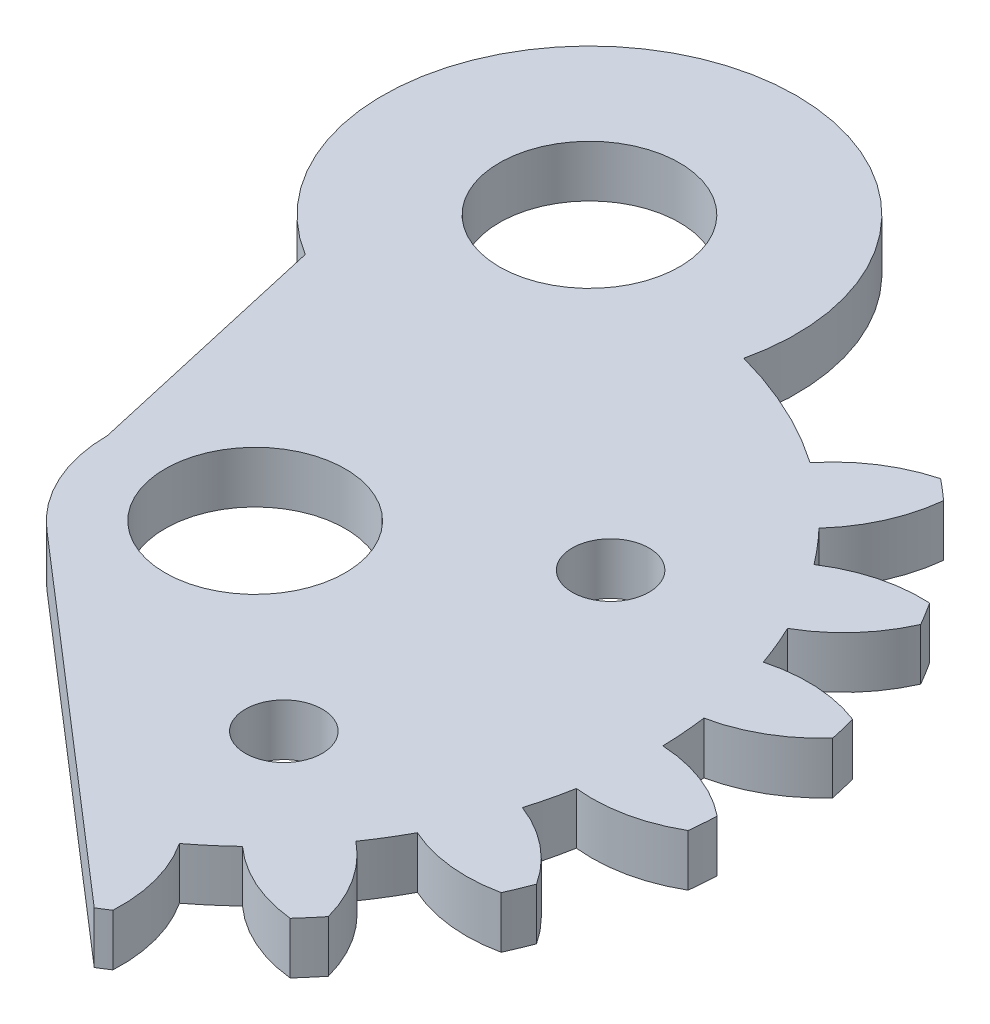
SolidWorks part; units mm, degrees
ref_plane "前视基准面" through (0, 0, 0) normal (0, 0, 1) x (1, 0, 0)
ref_plane "上视基准面" through (0, 0, 0) normal (0, 1, 0) x (1, 0, 0)
ref_plane "右视基准面" through (0, 0, 0) normal (1, 0, 0) x (0, 0, -1)
other "Configuration Table"
sketch "草图1" plane through (0, 0, 0) normal (0, 1, 0) x (1, 0, 0)
  line L0 (0, 0) -> (0, 56.9379) construction
  line L1 (0, 0) -> (19.4661, 53.4826) construction
  line L2 (0, 0) -> (4.4104, 56.0389) construction
  line L3 (0, 30) -> (9.6418, 26.4907) construction
  circle A0 centre (0, 0) radius 30 construction
  circle A1 centre (0, 0) radius 27
  circle A2 centre (0, 0) radius 33
  arc A3 (1.6756, 32.9574) -> (-0.6065, 26.9932) centre (9.6418, 26.4907) ccw
  arc A4 (3.5007, 32.8138) -> (4.8217, 26.566) centre (-5.3791, 27.6728) cw
  dimension "D1" = 60
  dimension "D2" = 3
  dimension "D3" = 3
  dimension "D4" = 20
  dimension "D5" = 4.5
extrude "凸台-拉伸2" add sketch "草图1" along normal blind 10 contours A1
sketch "草图3" plane through (0, 10, 0) normal (0, 1, 0) x (1, 0, 0)
  arc A0 (4.8217, 26.566) -> (3.5007, 32.8138) centre (-5.3791, 27.6728) ccw construction
  circle A1 centre (0, 0) radius 33
  circle A2 centre (0, 0) radius 33
  circle A3 centre (0, 0) radius 27
  circle A4 centre (0, 0) radius 27
  arc A5 (1.6756, 32.9574) -> (-0.6065, 26.9932) centre (9.6418, 26.4907) ccw construction
  arc A6 (4.8217, 26.566) -> (3.5007, 32.8138) centre (-5.3791, 27.6728) ccw
  arc A7 (1.6756, 32.9574) -> (-0.6065, 26.9932) centre (9.6418, 26.4907) ccw
  arc A8 (12.795, 23.7758) -> (13.4694, 30.126) centre (3.4356, 27.9806) ccw
  arc A9 (11.778, 30.8266) -> (7.7646, 25.8595) centre (17.356, 22.2146) ccw
  arc A10 (19.5159, 18.6582) -> (22.1196, 24.4892) centre (11.9139, 25.5495) ccw
  arc A11 (20.7275, 25.6782) -> (15.3755, 22.1944) centre (23.3712, 15.7641) ccw
  arc A12 (24.3264, 11.7143) -> (28.6046, 16.4553) centre (19.2261, 20.6174) ccw
  arc A13 (27.648, 18.0163) -> (21.4815, 16.3568) centre (27.0987, 7.7704) ccw
  arc A14 (26.7557, 3.6237) -> (32.2896, 6.8106) centre (24.6562, 13.6672) ccw
  arc A15 (31.8622, 8.5908) -> (25.4846, 8.9181) centre (28.1736, -0.9838) ccw
  arc A16 (26.566, -4.8217) -> (32.8138, -3.5007) centre (27.6728, 5.3791) ccw
  arc A17 (32.9574, -1.6756) -> (26.9932, 0.6065) centre (26.4907, -9.6418) ccw
  arc A18 (23.7758, -12.795) -> (30.126, -13.4694) centre (27.9806, -3.4356) ccw
  arc A19 (30.8266, -11.778) -> (25.8595, -7.7646) centre (22.2146, -17.356) ccw
  arc A20 (18.6582, -19.5159) -> (24.4892, -22.1196) centre (25.5495, -11.9139) ccw
  arc A21 (25.6782, -20.7275) -> (22.1944, -15.3755) centre (15.7641, -23.3712) ccw
  arc A22 (11.7143, -24.3264) -> (16.4553, -28.6046) centre (20.6174, -19.2261) ccw
  arc A23 (18.0163, -27.648) -> (16.3568, -21.4815) centre (7.7704, -27.0987) ccw
  arc A24 (3.6237, -26.7557) -> (6.8106, -32.2896) centre (13.6672, -24.6562) ccw
  arc A25 (8.5908, -31.8622) -> (8.9181, -25.4846) centre (-0.9838, -28.1736) ccw
  arc A26 (-4.8217, -26.566) -> (-3.5007, -32.8138) centre (5.3791, -27.6728) ccw
  arc A27 (-1.6756, -32.9574) -> (0.6065, -26.9932) centre (-9.6418, -26.4907) ccw
  arc A28 (-12.795, -23.7758) -> (-13.4694, -30.126) centre (-3.4356, -27.9806) ccw
  arc A29 (-11.778, -30.8266) -> (-7.7646, -25.8595) centre (-17.356, -22.2146) ccw
  arc A30 (-19.5159, -18.6582) -> (-22.1196, -24.4892) centre (-11.9139, -25.5495) ccw
  arc A31 (-20.7275, -25.6782) -> (-15.3755, -22.1944) centre (-23.3712, -15.7641) ccw
  arc A32 (-24.3264, -11.7143) -> (-28.6046, -16.4553) centre (-19.2261, -20.6174) ccw
  arc A33 (-27.648, -18.0163) -> (-21.4815, -16.3568) centre (-27.0987, -7.7704) ccw
  arc A34 (-26.7557, -3.6237) -> (-32.2896, -6.8106) centre (-24.6562, -13.6672) ccw
  arc A35 (-31.8622, -8.5908) -> (-25.4846, -8.9181) centre (-28.1736, 0.9838) ccw
  arc A36 (-26.566, 4.8217) -> (-32.8138, 3.5007) centre (-27.6728, -5.3791) ccw
  arc A37 (-32.9574, 1.6756) -> (-26.9932, -0.6065) centre (-26.4907, 9.6418) ccw
  arc A38 (-23.7758, 12.795) -> (-30.126, 13.4694) centre (-27.9806, 3.4356) ccw
  arc A39 (-30.8266, 11.778) -> (-25.8595, 7.7646) centre (-22.2146, 17.356) ccw
  arc A40 (-18.6582, 19.5159) -> (-24.4892, 22.1196) centre (-25.5495, 11.9139) ccw
  arc A41 (-25.6782, 20.7275) -> (-22.1944, 15.3755) centre (-15.7641, 23.3712) ccw
  arc A42 (-11.7143, 24.3264) -> (-16.4553, 28.6046) centre (-20.6174, 19.2261) ccw
  arc A43 (-18.0163, 27.648) -> (-16.3568, 21.4815) centre (-7.7704, 27.0987) ccw
  arc A44 (-3.6237, 26.7557) -> (-6.8106, 32.2896) centre (-13.6672, 24.6562) ccw
  arc A45 (-8.5908, 31.8622) -> (-8.9181, 25.4846) centre (0.9838, 28.1736) ccw
  point P129 (0, 0)
  circle M3 centre (0, 0) radius 27
  dimension "D1" = 0
  dimension "D2" = 0
  dimension "D3" = 20
extrude "凸台-拉伸3" add sketch "草图3" against normal blind 10 contours A2 A45 A44 M3 | A2 A43 A42 M3 | A2 A41 A40 M3 | A2 A39 A38 M3 | A2 A37 A36 M3 | A2 A35 A34 M3 | A2 A33 A32 M3 | A2 A31 A30 M3 | A2 A29 A28 M3 | A2 A27 A26 M3 | A2 A25 A24 M3 | A2 A23 A22 M3 | A2 A21 A20 M3 | A2 A19 A18 M3 | A2 A17 A16 M3 | A2 A15 A14 M3 | A2 A13 A12 M3 | A2 A11 A10 M3 | A2 A9 A8 M3 | A2 A7 A6 M3
sketch "草图4" plane through (0, 10, 0) normal (0, 1, 0) x (1, 0, 0)
  line L0 (0, 0) -> (23.0213, -14.1075)
  line L1 (0, 0) -> (-2.1184, 26.9168)
  line L2 (-9.5508, 2.9635) -> (19.9356, 97.9927)
  line L5 (-6.5422, -7.5631) -> (68.7094, -72.6568)
  arc A0 (16.4553, -28.6046) -> (18.0163, -27.648) centre (0, 0) ccw construction
  arc A1 (-0.6065, 26.9932) -> (-3.6237, 26.7557) centre (0, 0) ccw construction
  circle A2 centre (0, 0) radius 100
  arc A3 (22.1944, -15.3755) -> (23.7758, -12.795) centre (0, 0) ccw construction
  circle A4 centre (0, 0) radius 10
  point P9 (17.2425, -28.1371)
  point P18 (-2.1184, 26.9168)
  dimension "D1" = 20
  dimension "D2" = 200
extrude "切除-拉伸2" cut sketch "草图4" against normal through all
sketch "草图6" plane through (0, 10, 0) normal (0, 1, 0) x (1, 0, 0)
  line L2 (-6.5422, -7.5631) -> (17.2425, -28.1371)
  line L3 (-2.1184, 26.9168) -> (-9.5508, 2.9635)
  line L4 (-6.5422, -7.5631) -> (17.2425, -28.1371)
  line L5 (-2.1184, 26.9168) -> (-9.5508, 2.9635)
  circle A0 centre (0, 0) radius 6.1
  arc A22 (-9.5508, 2.9635) -> (-6.5422, -7.5631) centre (0, 0) ccw
  arc A23 (17.2425, -28.1371) -> (18.0163, -27.648) centre (0, 0) ccw
  arc A24 (30.8266, -11.778) -> (25.8595, -7.7646) centre (22.2146, -17.356) ccw
  arc A25 (25.8595, -7.7646) -> (26.566, -4.8217) centre (0, 0) ccw
  arc A26 (26.566, -4.8217) -> (32.8138, -3.5007) centre (27.6728, 5.3791) ccw
  arc A27 (32.8138, -3.5007) -> (32.9574, -1.6756) centre (0, 0) ccw
  arc A28 (32.9574, -1.6756) -> (26.9932, 0.6065) centre (26.4907, -9.6418) ccw
  arc A29 (26.9932, 0.6065) -> (26.7557, 3.6237) centre (0, 0) ccw
  arc A30 (26.7557, 3.6237) -> (32.2896, 6.8106) centre (24.6562, 13.6672) ccw
  arc A31 (32.2896, 6.8106) -> (31.8622, 8.5908) centre (0, 0) ccw
  arc A32 (31.8622, 8.5908) -> (25.4846, 8.9181) centre (28.1736, -0.9838) ccw
  arc A33 (25.4846, 8.9181) -> (24.3264, 11.7143) centre (0, 0) ccw
  arc A34 (24.3264, 11.7143) -> (28.6046, 16.4553) centre (19.2261, 20.6174) ccw
  arc A35 (28.6046, 16.4553) -> (27.648, 18.0163) centre (0, 0) ccw
  arc A36 (27.648, 18.0163) -> (21.4815, 16.3568) centre (27.0987, 7.7704) ccw
  arc A37 (21.4815, 16.3568) -> (19.5159, 18.6582) centre (0, 0) ccw
  arc A38 (19.5159, 18.6582) -> (22.1196, 24.4892) centre (11.9139, 25.5495) ccw
  arc A39 (22.1196, 24.4892) -> (20.7275, 25.6782) centre (0, 0) ccw
  arc A40 (20.7275, 25.6782) -> (15.3755, 22.1944) centre (23.3712, 15.7641) ccw
  arc A41 (15.3755, 22.1944) -> (12.795, 23.7758) centre (0, 0) ccw
  arc A42 (12.795, 23.7758) -> (13.4694, 30.126) centre (3.4356, 27.9806) ccw
  arc A43 (13.4694, 30.126) -> (11.778, 30.8266) centre (0, 0) ccw
  arc A44 (-9.5508, 2.9635) -> (-6.5422, -7.5631) centre (0, 0) ccw
  arc A45 (17.2425, -28.1371) -> (18.0163, -27.648) centre (0, 0) ccw
  arc A46 (30.8266, -11.778) -> (25.8595, -7.7646) centre (22.2146, -17.356) ccw
  arc A47 (25.8595, -7.7646) -> (26.566, -4.8217) centre (0, 0) ccw
  arc A48 (26.566, -4.8217) -> (32.8138, -3.5007) centre (27.6728, 5.3791) ccw
  arc A49 (32.8138, -3.5007) -> (32.9574, -1.6756) centre (0, 0) ccw
  arc A50 (32.9574, -1.6756) -> (26.9932, 0.6065) centre (26.4907, -9.6418) ccw
  arc A51 (26.9932, 0.6065) -> (26.7557, 3.6237) centre (0, 0) ccw
  arc A52 (26.7557, 3.6237) -> (32.2896, 6.8106) centre (24.6562, 13.6672) ccw
  arc A53 (32.2896, 6.8106) -> (31.8622, 8.5908) centre (0, 0) ccw
  arc A54 (31.8622, 8.5908) -> (25.4846, 8.9181) centre (28.1736, -0.9838) ccw
  arc A55 (25.4846, 8.9181) -> (24.3264, 11.7143) centre (0, 0) ccw
  arc A56 (24.3264, 11.7143) -> (28.6046, 16.4553) centre (19.2261, 20.6174) ccw
  arc A57 (28.6046, 16.4553) -> (27.648, 18.0163) centre (0, 0) ccw
  arc A58 (27.648, 18.0163) -> (21.4815, 16.3568) centre (27.0987, 7.7704) ccw
  arc A59 (21.4815, 16.3568) -> (19.5159, 18.6582) centre (0, 0) ccw
  arc A60 (19.5159, 18.6582) -> (22.1196, 24.4892) centre (11.9139, 25.5495) ccw
  arc A61 (22.1196, 24.4892) -> (20.7275, 25.6782) centre (0, 0) ccw
  arc A62 (20.7275, 25.6782) -> (15.3755, 22.1944) centre (23.3712, 15.7641) ccw
  arc A63 (15.3755, 22.1944) -> (12.795, 23.7758) centre (0, 0) ccw
  arc A64 (12.795, 23.7758) -> (13.4694, 30.126) centre (3.4356, 27.9806) ccw
  arc A65 (13.4694, 30.126) -> (11.778, 30.8266) centre (0, 0) ccw
  arc A73 (11.778, 30.8266) -> (7.7646, 25.8595) centre (17.356, 22.2146) ccw
  arc A74 (11.778, 30.8266) -> (7.7646, 25.8595) centre (17.356, 22.2146) ccw
  arc A75 (7.7646, 25.8595) -> (4.8217, 26.566) centre (0, 0) ccw
  arc A76 (7.7646, 25.8595) -> (4.8217, 26.566) centre (0, 0) ccw
  arc A77 (4.8217, 26.566) -> (3.5007, 32.8138) centre (-5.3791, 27.6728) ccw
  arc A78 (4.8217, 26.566) -> (3.5007, 32.8138) centre (-5.3791, 27.6728) ccw
  arc A79 (3.5007, 32.8138) -> (1.6756, 32.9574) centre (0, 0) ccw
  arc A80 (3.5007, 32.8138) -> (1.6756, 32.9574) centre (0, 0) ccw
  arc A81 (1.6756, 32.9574) -> (-0.6065, 26.9932) centre (9.6418, 26.4907) ccw
  arc A82 (1.6756, 32.9574) -> (-0.6065, 26.9932) centre (9.6418, 26.4907) ccw
  arc A83 (-0.6065, 26.9932) -> (-2.1184, 26.9168) centre (0, 0) ccw
  arc A84 (-0.6065, 26.9932) -> (-2.1184, 26.9168) centre (0, 0) ccw
  arc A89 (25.6782, -20.7275) -> (22.1944, -15.3755) centre (15.7641, -23.3712) ccw
  arc A90 (25.6782, -20.7275) -> (22.1944, -15.3755) centre (15.7641, -23.3712) ccw
  arc A91 (22.1944, -15.3755) -> (23.7758, -12.795) centre (0, 0) ccw
  arc A92 (22.1944, -15.3755) -> (23.7758, -12.795) centre (0, 0) ccw
  arc A93 (23.7758, -12.795) -> (30.126, -13.4694) centre (27.9806, -3.4356) ccw
  arc A94 (23.7758, -12.795) -> (30.126, -13.4694) centre (27.9806, -3.4356) ccw
  arc A95 (30.126, -13.4694) -> (30.8266, -11.778) centre (0, 0) ccw
  arc A96 (30.126, -13.4694) -> (30.8266, -11.778) centre (0, 0) ccw
  arc A101 (18.0163, -27.648) -> (16.3568, -21.4815) centre (7.7704, -27.0987) ccw
  arc A102 (18.0163, -27.648) -> (16.3568, -21.4815) centre (7.7704, -27.0987) ccw
  arc A103 (16.3568, -21.4815) -> (18.6582, -19.5159) centre (0, 0) ccw
  arc A104 (16.3568, -21.4815) -> (18.6582, -19.5159) centre (0, 0) ccw
  arc A105 (18.6582, -19.5159) -> (24.4892, -22.1196) centre (25.5495, -11.9139) ccw
  arc A106 (18.6582, -19.5159) -> (24.4892, -22.1196) centre (25.5495, -11.9139) ccw
  arc A107 (24.4892, -22.1196) -> (25.6782, -20.7275) centre (0, 0) ccw
  arc A108 (24.4892, -22.1196) -> (25.6782, -20.7275) centre (0, 0) ccw
  dimension "D2" = 12.2
  dimension "D1" = 0
extrude "切除-拉伸3" cut sketch "草图6" against normal blind 10 contours A0
sketch "草图9" plane through (0, 10, 0) normal (0, 1, 0) x (1, 0, 0)
  line L0 (-10, 0) -> (-18.3373, 36.811)
  line L1 (-6.5422, -7.5631) -> (4.8217, 26.566)
  line L2 (4.8217, 26.566) -> (7.168, 33.6128)
  line L3 (-6.5422, -7.5631) -> (17.2425, -28.1371)
  line L4 (-2.1184, 26.9168) -> (-9.5508, 2.9635)
  line L5 (-6.5422, -7.5631) -> (17.2425, -28.1371)
  line L6 (-2.1184, 26.9168) -> (-9.5508, 2.9635)
  arc A0 (-9.5508, 2.9635) -> (-6.5422, -7.5631) centre (0, 0) ccw construction
  circle A1 centre (-10, 0) radius 37.7433
  arc A42 (-9.5508, 2.9635) -> (-6.5422, -7.5631) centre (0, 0) ccw
  arc A43 (17.2425, -28.1371) -> (18.0163, -27.648) centre (0, 0) ccw
  arc A48 (18.0163, -27.648) -> (16.3568, -21.4815) centre (7.7704, -27.0987) ccw
  arc A49 (16.3568, -21.4815) -> (18.6582, -19.5159) centre (0, 0) ccw
  arc A50 (18.6582, -19.5159) -> (24.4892, -22.1196) centre (25.5495, -11.9139) ccw
  arc A51 (24.4892, -22.1196) -> (25.6782, -20.7275) centre (0, 0) ccw
  arc A52 (25.6782, -20.7275) -> (22.1944, -15.3755) centre (15.7641, -23.3712) ccw
  arc A53 (22.1944, -15.3755) -> (23.7758, -12.795) centre (0, 0) ccw
  arc A54 (23.7758, -12.795) -> (30.126, -13.4694) centre (27.9806, -3.4356) ccw
  arc A55 (30.126, -13.4694) -> (30.8266, -11.778) centre (0, 0) ccw
  arc A56 (30.8266, -11.778) -> (25.8595, -7.7646) centre (22.2146, -17.356) ccw
  arc A57 (25.8595, -7.7646) -> (26.566, -4.8217) centre (0, 0) ccw
  arc A58 (26.566, -4.8217) -> (32.8138, -3.5007) centre (27.6728, 5.3791) ccw
  arc A59 (32.8138, -3.5007) -> (32.9574, -1.6756) centre (0, 0) ccw
  arc A60 (32.9574, -1.6756) -> (26.9932, 0.6065) centre (26.4907, -9.6418) ccw
  arc A61 (26.9932, 0.6065) -> (26.7557, 3.6237) centre (0, 0) ccw
  arc A62 (26.7557, 3.6237) -> (32.2896, 6.8106) centre (24.6562, 13.6672) ccw
  arc A63 (32.2896, 6.8106) -> (31.8622, 8.5908) centre (0, 0) ccw
  arc A64 (31.8622, 8.5908) -> (25.4846, 8.9181) centre (28.1736, -0.9838) ccw
  arc A65 (25.4846, 8.9181) -> (24.3264, 11.7143) centre (0, 0) ccw
  arc A66 (24.3264, 11.7143) -> (28.6046, 16.4553) centre (19.2261, 20.6174) ccw
  arc A67 (28.6046, 16.4553) -> (27.648, 18.0163) centre (0, 0) ccw
  arc A68 (27.648, 18.0163) -> (21.4815, 16.3568) centre (27.0987, 7.7704) ccw
  arc A69 (21.4815, 16.3568) -> (19.5159, 18.6582) centre (0, 0) ccw
  arc A70 (19.5159, 18.6582) -> (22.1196, 24.4892) centre (11.9139, 25.5495) ccw
  arc A71 (22.1196, 24.4892) -> (20.7275, 25.6782) centre (0, 0) ccw
  arc A72 (20.7275, 25.6782) -> (15.3755, 22.1944) centre (23.3712, 15.7641) ccw
  arc A73 (15.3755, 22.1944) -> (12.795, 23.7758) centre (0, 0) ccw
  arc A74 (12.795, 23.7758) -> (13.4694, 30.126) centre (3.4356, 27.9806) ccw
  arc A75 (13.4694, 30.126) -> (11.778, 30.8266) centre (0, 0) ccw
  arc A76 (11.778, 30.8266) -> (7.7646, 25.8595) centre (17.356, 22.2146) ccw
  arc A77 (7.7646, 25.8595) -> (4.8217, 26.566) centre (0, 0) ccw
  arc A78 (4.8217, 26.566) -> (3.5007, 32.8138) centre (-5.3791, 27.6728) ccw
  arc A79 (3.5007, 32.8138) -> (1.6756, 32.9574) centre (0, 0) ccw
  arc A80 (1.6756, 32.9574) -> (-0.6065, 26.9932) centre (9.6418, 26.4907) ccw
  arc A81 (-0.6065, 26.9932) -> (-2.1184, 26.9168) centre (0, 0) ccw
  arc A82 (-9.5508, 2.9635) -> (-6.5422, -7.5631) centre (0, 0) ccw
  arc A83 (17.2425, -28.1371) -> (18.0163, -27.648) centre (0, 0) ccw
  arc A88 (18.0163, -27.648) -> (16.3568, -21.4815) centre (7.7704, -27.0987) ccw
  arc A89 (16.3568, -21.4815) -> (18.6582, -19.5159) centre (0, 0) ccw
  arc A90 (18.6582, -19.5159) -> (24.4892, -22.1196) centre (25.5495, -11.9139) ccw
  arc A91 (24.4892, -22.1196) -> (25.6782, -20.7275) centre (0, 0) ccw
  arc A92 (25.6782, -20.7275) -> (22.1944, -15.3755) centre (15.7641, -23.3712) ccw
  arc A93 (22.1944, -15.3755) -> (23.7758, -12.795) centre (0, 0) ccw
  arc A94 (23.7758, -12.795) -> (30.126, -13.4694) centre (27.9806, -3.4356) ccw
  arc A95 (30.126, -13.4694) -> (30.8266, -11.778) centre (0, 0) ccw
  arc A96 (30.8266, -11.778) -> (25.8595, -7.7646) centre (22.2146, -17.356) ccw
  arc A97 (25.8595, -7.7646) -> (26.566, -4.8217) centre (0, 0) ccw
  arc A98 (26.566, -4.8217) -> (32.8138, -3.5007) centre (27.6728, 5.3791) ccw
  arc A99 (32.8138, -3.5007) -> (32.9574, -1.6756) centre (0, 0) ccw
  arc A100 (32.9574, -1.6756) -> (26.9932, 0.6065) centre (26.4907, -9.6418) ccw
  arc A101 (26.9932, 0.6065) -> (26.7557, 3.6237) centre (0, 0) ccw
  arc A102 (26.7557, 3.6237) -> (32.2896, 6.8106) centre (24.6562, 13.6672) ccw
  arc A103 (32.2896, 6.8106) -> (31.8622, 8.5908) centre (0, 0) ccw
  arc A104 (31.8622, 8.5908) -> (25.4846, 8.9181) centre (28.1736, -0.9838) ccw
  arc A105 (25.4846, 8.9181) -> (24.3264, 11.7143) centre (0, 0) ccw
  arc A106 (24.3264, 11.7143) -> (28.6046, 16.4553) centre (19.2261, 20.6174) ccw
  arc A107 (28.6046, 16.4553) -> (27.648, 18.0163) centre (0, 0) ccw
  arc A108 (27.648, 18.0163) -> (21.4815, 16.3568) centre (27.0987, 7.7704) ccw
  arc A109 (21.4815, 16.3568) -> (19.5159, 18.6582) centre (0, 0) ccw
  arc A110 (19.5159, 18.6582) -> (22.1196, 24.4892) centre (11.9139, 25.5495) ccw
  arc A111 (22.1196, 24.4892) -> (20.7275, 25.6782) centre (0, 0) ccw
  arc A112 (20.7275, 25.6782) -> (15.3755, 22.1944) centre (23.3712, 15.7641) ccw
  arc A113 (15.3755, 22.1944) -> (12.795, 23.7758) centre (0, 0) ccw
  arc A114 (12.795, 23.7758) -> (13.4694, 30.126) centre (3.4356, 27.9806) ccw
  arc A115 (13.4694, 30.126) -> (11.778, 30.8266) centre (0, 0) ccw
  arc A116 (11.778, 30.8266) -> (7.7646, 25.8595) centre (17.356, 22.2146) ccw
  arc A117 (7.7646, 25.8595) -> (4.8217, 26.566) centre (0, 0) ccw
  arc A118 (4.8217, 26.566) -> (3.5007, 32.8138) centre (-5.3791, 27.6728) ccw
  arc A119 (3.5007, 32.8138) -> (1.6756, 32.9574) centre (0, 0) ccw
  arc A120 (1.6756, 32.9574) -> (-0.6065, 26.9932) centre (9.6418, 26.4907) ccw
  arc A121 (-0.6065, 26.9932) -> (-2.1184, 26.9168) centre (0, 0) ccw
  arc M46 (-9.5508, 2.9635) -> (-6.5422, -7.5631) centre (0, 0) ccw
  arc M81 (11.778, 30.8266) -> (7.7646, 25.8595) centre (17.356, 22.2146) ccw
  arc M82 (7.7646, 25.8595) -> (4.8217, 26.566) centre (0, 0) ccw
  arc M83 (4.8217, 26.566) -> (3.5007, 32.8138) centre (-5.3791, 27.6728) ccw
  arc M84 (3.5007, 32.8138) -> (1.6756, 32.9574) centre (0, 0) ccw
  arc M85 (1.6756, 32.9574) -> (-0.6065, 26.9932) centre (9.6418, 26.4907) ccw
  arc M86 (-0.6065, 26.9932) -> (-2.1184, 26.9168) centre (0, 0) ccw
  line M87 (-2.1184, 26.9168) -> (-9.5508, 2.9635)
  dimension "D1" = 0
  dimension "D2" = 30
extrude "凸台-拉伸5" add sketch "草图9" against normal blind 10 contours A1 L0 M81 M46 M87 M86 M85 M84 M83 M82
sketch "草图10" plane through (0, 10, 0) normal (0, 1, 0) x (1, 0, 0)
  line L0 (-6.6268, 29.2589) -> (0, 0)
  line L1 (-10, 0) -> (-18.3373, 36.811) construction
  circle A0 centre (-6.6268, 29.2589) radius 6.1
  dimension "D1" = 12.2
  dimension "D2" = 30
extrude "切除-拉伸5" cut sketch "草图10" against normal blind 10
sketch "草图11" plane through (0, 10, 0) normal (0, 1, 0) x (1, 0, 0)
  line L0 (3.5007, 32.8138) -> (0, 36.3945)
  line L1 (0, 0) -> (0, 56.9379) construction
  line L5 (-18.3373, 36.811) -> (-10, 0)
  line L6 (-6.5422, -7.5631) -> (17.2425, -28.1371)
  line L7 (4.8217, 26.566) -> (7.168, 33.6128)
  line L8 (-18.3373, 36.811) -> (-10, 0)
  line L9 (-6.5422, -7.5631) -> (17.2425, -28.1371)
  line L10 (4.8217, 26.566) -> (7.168, 33.6128)
  arc A0 (4.8217, 26.566) -> (3.5007, 32.8138) centre (-5.3791, 27.6728) ccw construction
  arc A1 (4.8217, 26.566) -> (3.5007, 32.8138) centre (-5.3791, 27.6728) ccw
  arc A2 (7.168, 33.6128) -> (-18.3373, 36.811) centre (-10, 0) ccw construction
  arc A40 (-10, 0) -> (-6.5422, -7.5631) centre (0, 0) ccw
  arc A41 (17.2425, -28.1371) -> (18.0163, -27.648) centre (0, 0) ccw
  arc A46 (18.0163, -27.648) -> (16.3568, -21.4815) centre (7.7704, -27.0987) ccw
  arc A47 (16.3568, -21.4815) -> (18.6582, -19.5159) centre (0, 0) ccw
  arc A48 (18.6582, -19.5159) -> (24.4892, -22.1196) centre (25.5495, -11.9139) ccw
  arc A49 (24.4892, -22.1196) -> (25.6782, -20.7275) centre (0, 0) ccw
  arc A50 (25.6782, -20.7275) -> (22.1944, -15.3755) centre (15.7641, -23.3712) ccw
  arc A51 (22.1944, -15.3755) -> (23.7758, -12.795) centre (0, 0) ccw
  arc A52 (23.7758, -12.795) -> (30.126, -13.4694) centre (27.9806, -3.4356) ccw
  arc A53 (30.126, -13.4694) -> (30.8266, -11.778) centre (0, 0) ccw
  arc A54 (30.8266, -11.778) -> (25.8595, -7.7646) centre (22.2146, -17.356) ccw
  arc A55 (25.8595, -7.7646) -> (26.566, -4.8217) centre (0, 0) ccw
  arc A56 (26.566, -4.8217) -> (32.8138, -3.5007) centre (27.6728, 5.3791) ccw
  arc A57 (32.8138, -3.5007) -> (32.9574, -1.6756) centre (0, 0) ccw
  arc A58 (32.9574, -1.6756) -> (26.9932, 0.6065) centre (26.4907, -9.6418) ccw
  arc A59 (26.9932, 0.6065) -> (26.7557, 3.6237) centre (0, 0) ccw
  arc A60 (26.7557, 3.6237) -> (32.2896, 6.8106) centre (24.6562, 13.6672) ccw
  arc A61 (32.2896, 6.8106) -> (31.8622, 8.5908) centre (0, 0) ccw
  arc A62 (31.8622, 8.5908) -> (25.4846, 8.9181) centre (28.1736, -0.9838) ccw
  arc A63 (25.4846, 8.9181) -> (24.3264, 11.7143) centre (0, 0) ccw
  arc A64 (24.3264, 11.7143) -> (28.6046, 16.4553) centre (19.2261, 20.6174) ccw
  arc A65 (28.6046, 16.4553) -> (27.648, 18.0163) centre (0, 0) ccw
  arc A66 (27.648, 18.0163) -> (21.4815, 16.3568) centre (27.0987, 7.7704) ccw
  arc A67 (21.4815, 16.3568) -> (19.5159, 18.6582) centre (0, 0) ccw
  arc A68 (19.5159, 18.6582) -> (22.1196, 24.4892) centre (11.9139, 25.5495) ccw
  arc A69 (22.1196, 24.4892) -> (20.7275, 25.6782) centre (0, 0) ccw
  arc A70 (20.7275, 25.6782) -> (15.3755, 22.1944) centre (23.3712, 15.7641) ccw
  arc A71 (15.3755, 22.1944) -> (12.795, 23.7758) centre (0, 0) ccw
  arc A72 (12.795, 23.7758) -> (13.4694, 30.126) centre (3.4356, 27.9806) ccw
  arc A73 (13.4694, 30.126) -> (11.778, 30.8266) centre (0, 0) ccw
  arc A74 (11.778, 30.8266) -> (7.7646, 25.8595) centre (17.356, 22.2146) ccw
  arc A75 (7.7646, 25.8595) -> (4.8217, 26.566) centre (0, 0) ccw
  arc A76 (7.168, 33.6128) -> (-18.3373, 36.811) centre (-10, 0) ccw
  arc A77 (-10, 0) -> (-6.5422, -7.5631) centre (0, 0) ccw
  arc A78 (17.2425, -28.1371) -> (18.0163, -27.648) centre (0, 0) ccw
  arc A83 (18.0163, -27.648) -> (16.3568, -21.4815) centre (7.7704, -27.0987) ccw
  arc A84 (16.3568, -21.4815) -> (18.6582, -19.5159) centre (0, 0) ccw
  arc A85 (18.6582, -19.5159) -> (24.4892, -22.1196) centre (25.5495, -11.9139) ccw
  arc A86 (24.4892, -22.1196) -> (25.6782, -20.7275) centre (0, 0) ccw
  arc A87 (25.6782, -20.7275) -> (22.1944, -15.3755) centre (15.7641, -23.3712) ccw
  arc A88 (22.1944, -15.3755) -> (23.7758, -12.795) centre (0, 0) ccw
  arc A89 (23.7758, -12.795) -> (30.126, -13.4694) centre (27.9806, -3.4356) ccw
  arc A90 (30.126, -13.4694) -> (30.8266, -11.778) centre (0, 0) ccw
  arc A91 (30.8266, -11.778) -> (25.8595, -7.7646) centre (22.2146, -17.356) ccw
  arc A92 (25.8595, -7.7646) -> (26.566, -4.8217) centre (0, 0) ccw
  arc A93 (26.566, -4.8217) -> (32.8138, -3.5007) centre (27.6728, 5.3791) ccw
  arc A94 (32.8138, -3.5007) -> (32.9574, -1.6756) centre (0, 0) ccw
  arc A95 (32.9574, -1.6756) -> (26.9932, 0.6065) centre (26.4907, -9.6418) ccw
  arc A96 (26.9932, 0.6065) -> (26.7557, 3.6237) centre (0, 0) ccw
  arc A97 (26.7557, 3.6237) -> (32.2896, 6.8106) centre (24.6562, 13.6672) ccw
  arc A98 (32.2896, 6.8106) -> (31.8622, 8.5908) centre (0, 0) ccw
  arc A99 (31.8622, 8.5908) -> (25.4846, 8.9181) centre (28.1736, -0.9838) ccw
  arc A100 (25.4846, 8.9181) -> (24.3264, 11.7143) centre (0, 0) ccw
  arc A101 (24.3264, 11.7143) -> (28.6046, 16.4553) centre (19.2261, 20.6174) ccw
  arc A102 (28.6046, 16.4553) -> (27.648, 18.0163) centre (0, 0) ccw
  arc A103 (27.648, 18.0163) -> (21.4815, 16.3568) centre (27.0987, 7.7704) ccw
  arc A104 (21.4815, 16.3568) -> (19.5159, 18.6582) centre (0, 0) ccw
  arc A105 (19.5159, 18.6582) -> (22.1196, 24.4892) centre (11.9139, 25.5495) ccw
  arc A106 (22.1196, 24.4892) -> (20.7275, 25.6782) centre (0, 0) ccw
  arc A107 (20.7275, 25.6782) -> (15.3755, 22.1944) centre (23.3712, 15.7641) ccw
  arc A108 (15.3755, 22.1944) -> (12.795, 23.7758) centre (0, 0) ccw
  arc A109 (12.795, 23.7758) -> (13.4694, 30.126) centre (3.4356, 27.9806) ccw
  arc A110 (13.4694, 30.126) -> (11.778, 30.8266) centre (0, 0) ccw
  arc A111 (11.778, 30.8266) -> (7.7646, 25.8595) centre (17.356, 22.2146) ccw
  arc A112 (7.7646, 25.8595) -> (4.8217, 26.566) centre (0, 0) ccw
  arc A113 (7.168, 33.6128) -> (-18.3373, 36.811) centre (-10, 0) ccw
  line M80 (4.8217, 26.566) -> (7.168, 33.6128)
  arc M81 (7.168, 33.6128) -> (-18.3373, 36.811) centre (-10, 0) ccw
  dimension "D1" = 0
extrude "切除-拉伸6" cut sketch "草图11" against normal blind 10 contours A1 L0 M80 M81
fillet "圆角1" radius 10 1 edges at (-18.3373, 5, -36.811)
sketch "草图16" plane through (0, 10, 0) normal (0, 1, 0) x (1, 0, 0)
  line L3 (-15.7164, 25.2392) -> (-10, 0)
  line L4 (-6.5422, -7.5631) -> (17.2425, -28.1371)
  line L5 (3.5007, 32.8138) -> (0, 36.3945)
  line L6 (-15.7164, 25.2392) -> (-10, 0)
  line L7 (-6.5422, -7.5631) -> (17.2425, -28.1371)
  line L8 (3.5007, 32.8138) -> (0, 36.3945)
  circle A0 centre (-6.6268, 29.2589) radius 6.1 construction
  circle A1 centre (-6.6268, 29.2589) radius 6.1
  circle A2 centre (-6.6268, 29.2589) radius 14
  arc A38 (0, 36.3945) -> (-4.5084, 37.3417) centre (-10, 0) ccw
  arc A39 (-4.5084, 37.3417) -> (-15.7164, 25.2392) centre (-5.9634, 27.4481) ccw
  arc A40 (-10, 0) -> (-6.5422, -7.5631) centre (0, 0) ccw
  arc A41 (17.2425, -28.1371) -> (18.0163, -27.648) centre (0, 0) ccw
  arc A42 (18.0163, -27.648) -> (16.3568, -21.4815) centre (7.7704, -27.0987) ccw
  arc A43 (16.3568, -21.4815) -> (18.6582, -19.5159) centre (0, 0) ccw
  arc A44 (18.6582, -19.5159) -> (24.4892, -22.1196) centre (25.5495, -11.9139) ccw
  arc A45 (24.4892, -22.1196) -> (25.6782, -20.7275) centre (0, 0) ccw
  arc A46 (25.6782, -20.7275) -> (22.1944, -15.3755) centre (15.7641, -23.3712) ccw
  arc A47 (22.1944, -15.3755) -> (23.7758, -12.795) centre (0, 0) ccw
  arc A48 (23.7758, -12.795) -> (30.126, -13.4694) centre (27.9806, -3.4356) ccw
  arc A49 (30.126, -13.4694) -> (30.8266, -11.778) centre (0, 0) ccw
  arc A50 (30.8266, -11.778) -> (25.8595, -7.7646) centre (22.2146, -17.356) ccw
  arc A51 (25.8595, -7.7646) -> (26.566, -4.8217) centre (0, 0) ccw
  arc A52 (26.566, -4.8217) -> (32.8138, -3.5007) centre (27.6728, 5.3791) ccw
  arc A53 (32.8138, -3.5007) -> (32.9574, -1.6756) centre (0, 0) ccw
  arc A54 (32.9574, -1.6756) -> (26.9932, 0.6065) centre (26.4907, -9.6418) ccw
  arc A55 (26.9932, 0.6065) -> (26.7557, 3.6237) centre (0, 0) ccw
  arc A56 (26.7557, 3.6237) -> (32.2896, 6.8106) centre (24.6562, 13.6672) ccw
  arc A57 (32.2896, 6.8106) -> (31.8622, 8.5908) centre (0, 0) ccw
  arc A58 (31.8622, 8.5908) -> (25.4846, 8.9181) centre (28.1736, -0.9838) ccw
  arc A59 (25.4846, 8.9181) -> (24.3264, 11.7143) centre (0, 0) ccw
  arc A60 (24.3264, 11.7143) -> (28.6046, 16.4553) centre (19.2261, 20.6174) ccw
  arc A61 (28.6046, 16.4553) -> (27.648, 18.0163) centre (0, 0) ccw
  arc A62 (27.648, 18.0163) -> (21.4815, 16.3568) centre (27.0987, 7.7704) ccw
  arc A63 (21.4815, 16.3568) -> (19.5159, 18.6582) centre (0, 0) ccw
  arc A64 (19.5159, 18.6582) -> (22.1196, 24.4892) centre (11.9139, 25.5495) ccw
  arc A65 (22.1196, 24.4892) -> (20.7275, 25.6782) centre (0, 0) ccw
  arc A66 (20.7275, 25.6782) -> (15.3755, 22.1944) centre (23.3712, 15.7641) ccw
  arc A67 (15.3755, 22.1944) -> (12.795, 23.7758) centre (0, 0) ccw
  arc A68 (12.795, 23.7758) -> (13.4694, 30.126) centre (3.4356, 27.9806) ccw
  arc A69 (13.4694, 30.126) -> (11.778, 30.8266) centre (0, 0) ccw
  arc A70 (11.778, 30.8266) -> (7.7646, 25.8595) centre (17.356, 22.2146) ccw
  arc A71 (7.7646, 25.8595) -> (4.8217, 26.566) centre (0, 0) ccw
  arc A72 (4.8217, 26.566) -> (3.5007, 32.8138) centre (-5.3791, 27.6728) ccw
  arc A73 (0, 36.3945) -> (-4.5084, 37.3417) centre (-10, 0) ccw
  arc A74 (-4.5084, 37.3417) -> (-15.7164, 25.2392) centre (-5.9634, 27.4481) ccw
  arc A75 (-10, 0) -> (-6.5422, -7.5631) centre (0, 0) ccw
  arc A76 (17.2425, -28.1371) -> (18.0163, -27.648) centre (0, 0) ccw
  arc A77 (18.0163, -27.648) -> (16.3568, -21.4815) centre (7.7704, -27.0987) ccw
  arc A78 (16.3568, -21.4815) -> (18.6582, -19.5159) centre (0, 0) ccw
  arc A79 (18.6582, -19.5159) -> (24.4892, -22.1196) centre (25.5495, -11.9139) ccw
  arc A80 (24.4892, -22.1196) -> (25.6782, -20.7275) centre (0, 0) ccw
  arc A81 (25.6782, -20.7275) -> (22.1944, -15.3755) centre (15.7641, -23.3712) ccw
  arc A82 (22.1944, -15.3755) -> (23.7758, -12.795) centre (0, 0) ccw
  arc A83 (23.7758, -12.795) -> (30.126, -13.4694) centre (27.9806, -3.4356) ccw
  arc A84 (30.126, -13.4694) -> (30.8266, -11.778) centre (0, 0) ccw
  arc A85 (30.8266, -11.778) -> (25.8595, -7.7646) centre (22.2146, -17.356) ccw
  arc A86 (25.8595, -7.7646) -> (26.566, -4.8217) centre (0, 0) ccw
  arc A87 (26.566, -4.8217) -> (32.8138, -3.5007) centre (27.6728, 5.3791) ccw
  arc A88 (32.8138, -3.5007) -> (32.9574, -1.6756) centre (0, 0) ccw
  arc A89 (32.9574, -1.6756) -> (26.9932, 0.6065) centre (26.4907, -9.6418) ccw
  arc A90 (26.9932, 0.6065) -> (26.7557, 3.6237) centre (0, 0) ccw
  arc A91 (26.7557, 3.6237) -> (32.2896, 6.8106) centre (24.6562, 13.6672) ccw
  arc A92 (32.2896, 6.8106) -> (31.8622, 8.5908) centre (0, 0) ccw
  arc A93 (31.8622, 8.5908) -> (25.4846, 8.9181) centre (28.1736, -0.9838) ccw
  arc A94 (25.4846, 8.9181) -> (24.3264, 11.7143) centre (0, 0) ccw
  arc A95 (24.3264, 11.7143) -> (28.6046, 16.4553) centre (19.2261, 20.6174) ccw
  arc A96 (28.6046, 16.4553) -> (27.648, 18.0163) centre (0, 0) ccw
  arc A97 (27.648, 18.0163) -> (21.4815, 16.3568) centre (27.0987, 7.7704) ccw
  arc A98 (21.4815, 16.3568) -> (19.5159, 18.6582) centre (0, 0) ccw
  arc A99 (19.5159, 18.6582) -> (22.1196, 24.4892) centre (11.9139, 25.5495) ccw
  arc A100 (22.1196, 24.4892) -> (20.7275, 25.6782) centre (0, 0) ccw
  arc A101 (20.7275, 25.6782) -> (15.3755, 22.1944) centre (23.3712, 15.7641) ccw
  arc A102 (15.3755, 22.1944) -> (12.795, 23.7758) centre (0, 0) ccw
  arc A103 (12.795, 23.7758) -> (13.4694, 30.126) centre (3.4356, 27.9806) ccw
  arc A104 (13.4694, 30.126) -> (11.778, 30.8266) centre (0, 0) ccw
  arc A105 (11.778, 30.8266) -> (7.7646, 25.8595) centre (17.356, 22.2146) ccw
  arc A106 (7.7646, 25.8595) -> (4.8217, 26.566) centre (0, 0) ccw
  arc A107 (4.8217, 26.566) -> (3.5007, 32.8138) centre (-5.3791, 27.6728) ccw
  arc M42 (0, 36.3945) -> (-4.5084, 37.3417) centre (-10, 0) ccw
  arc M43 (-4.5084, 37.3417) -> (-15.7164, 25.2392) centre (-5.9634, 27.4481) ccw
  line M44 (-15.7164, 25.2392) -> (-10, 0)
  arc M78 (4.8217, 26.566) -> (3.5007, 32.8138) centre (-5.3791, 27.6728) ccw
  line M79 (3.5007, 32.8138) -> (0, 36.3945)
  dimension "D2" = 28
  dimension "D1" = 0
extrude "凸台-拉伸7" add sketch "草图16" against normal blind 10 contours A2 M78 M44 M43 M42 M79
sketch "草图17" plane through (0, 10, 0) normal (0, 1, 0) x (1, 0, 0)
  line L2 (-13.9202, 17.3088) -> (-10, 0)
  line L3 (-6.5422, -7.5631) -> (17.2425, -28.1371)
  line L4 (-13.9202, 17.3088) -> (-10, 0)
  line L5 (-6.5422, -7.5631) -> (17.2425, -28.1371)
  arc A33 (7.0064, 26.0751) -> (-13.9202, 17.3088) centre (-6.6268, 29.2589) ccw
  arc A34 (-10, 0) -> (-6.5422, -7.5631) centre (0, 0) ccw
  arc A35 (17.2425, -28.1371) -> (18.0163, -27.648) centre (0, 0) ccw
  arc A36 (18.0163, -27.648) -> (16.3568, -21.4815) centre (7.7704, -27.0987) ccw
  arc A37 (16.3568, -21.4815) -> (18.6582, -19.5159) centre (0, 0) ccw
  arc A38 (18.6582, -19.5159) -> (24.4892, -22.1196) centre (25.5495, -11.9139) ccw
  arc A39 (24.4892, -22.1196) -> (25.6782, -20.7275) centre (0, 0) ccw
  arc A40 (25.6782, -20.7275) -> (22.1944, -15.3755) centre (15.7641, -23.3712) ccw
  arc A41 (22.1944, -15.3755) -> (23.7758, -12.795) centre (0, 0) ccw
  arc A42 (23.7758, -12.795) -> (30.126, -13.4694) centre (27.9806, -3.4356) ccw
  arc A43 (30.126, -13.4694) -> (30.8266, -11.778) centre (0, 0) ccw
  arc A44 (30.8266, -11.778) -> (25.8595, -7.7646) centre (22.2146, -17.356) ccw
  arc A45 (25.8595, -7.7646) -> (26.566, -4.8217) centre (0, 0) ccw
  arc A46 (26.566, -4.8217) -> (32.8138, -3.5007) centre (27.6728, 5.3791) ccw
  arc A47 (32.8138, -3.5007) -> (32.9574, -1.6756) centre (0, 0) ccw
  arc A48 (32.9574, -1.6756) -> (26.9932, 0.6065) centre (26.4907, -9.6418) ccw
  arc A49 (26.9932, 0.6065) -> (26.7557, 3.6237) centre (0, 0) ccw
  arc A50 (26.7557, 3.6237) -> (32.2896, 6.8106) centre (24.6562, 13.6672) ccw
  arc A51 (32.2896, 6.8106) -> (31.8622, 8.5908) centre (0, 0) ccw
  arc A52 (31.8622, 8.5908) -> (25.4846, 8.9181) centre (28.1736, -0.9838) ccw
  arc A53 (25.4846, 8.9181) -> (24.3264, 11.7143) centre (0, 0) ccw
  arc A54 (24.3264, 11.7143) -> (28.6046, 16.4553) centre (19.2261, 20.6174) ccw
  arc A55 (28.6046, 16.4553) -> (27.648, 18.0163) centre (0, 0) ccw
  arc A56 (27.648, 18.0163) -> (21.4815, 16.3568) centre (27.0987, 7.7704) ccw
  arc A57 (21.4815, 16.3568) -> (19.5159, 18.6582) centre (0, 0) ccw
  arc A58 (19.5159, 18.6582) -> (22.1196, 24.4892) centre (11.9139, 25.5495) ccw
  arc A59 (22.1196, 24.4892) -> (20.7275, 25.6782) centre (0, 0) ccw
  arc A60 (20.7275, 25.6782) -> (15.3755, 22.1944) centre (23.3712, 15.7641) ccw
  arc A61 (15.3755, 22.1944) -> (12.795, 23.7758) centre (0, 0) ccw
  arc A62 (12.795, 23.7758) -> (13.4694, 30.126) centre (3.4356, 27.9806) ccw
  arc A63 (13.4694, 30.126) -> (11.778, 30.8266) centre (0, 0) ccw
  arc A64 (11.778, 30.8266) -> (7.7646, 25.8595) centre (17.356, 22.2146) ccw
  arc A65 (7.7646, 25.8595) -> (7.0064, 26.0751) centre (0, 0) ccw
  arc A66 (7.0064, 26.0751) -> (-13.9202, 17.3088) centre (-6.6268, 29.2589) ccw
  arc A67 (-10, 0) -> (-6.5422, -7.5631) centre (0, 0) ccw
  arc A68 (17.2425, -28.1371) -> (18.0163, -27.648) centre (0, 0) ccw
  arc A69 (18.0163, -27.648) -> (16.3568, -21.4815) centre (7.7704, -27.0987) ccw
  arc A70 (16.3568, -21.4815) -> (18.6582, -19.5159) centre (0, 0) ccw
  arc A71 (18.6582, -19.5159) -> (24.4892, -22.1196) centre (25.5495, -11.9139) ccw
  arc A72 (24.4892, -22.1196) -> (25.6782, -20.7275) centre (0, 0) ccw
  arc A73 (25.6782, -20.7275) -> (22.1944, -15.3755) centre (15.7641, -23.3712) ccw
  arc A74 (22.1944, -15.3755) -> (23.7758, -12.795) centre (0, 0) ccw
  arc A75 (23.7758, -12.795) -> (30.126, -13.4694) centre (27.9806, -3.4356) ccw
  arc A76 (30.126, -13.4694) -> (30.8266, -11.778) centre (0, 0) ccw
  arc A77 (30.8266, -11.778) -> (25.8595, -7.7646) centre (22.2146, -17.356) ccw
  arc A78 (25.8595, -7.7646) -> (26.566, -4.8217) centre (0, 0) ccw
  arc A79 (26.566, -4.8217) -> (32.8138, -3.5007) centre (27.6728, 5.3791) ccw
  arc A80 (32.8138, -3.5007) -> (32.9574, -1.6756) centre (0, 0) ccw
  arc A81 (32.9574, -1.6756) -> (26.9932, 0.6065) centre (26.4907, -9.6418) ccw
  arc A82 (26.9932, 0.6065) -> (26.7557, 3.6237) centre (0, 0) ccw
  arc A83 (26.7557, 3.6237) -> (32.2896, 6.8106) centre (24.6562, 13.6672) ccw
  arc A84 (32.2896, 6.8106) -> (31.8622, 8.5908) centre (0, 0) ccw
  arc A85 (31.8622, 8.5908) -> (25.4846, 8.9181) centre (28.1736, -0.9838) ccw
  arc A86 (25.4846, 8.9181) -> (24.3264, 11.7143) centre (0, 0) ccw
  arc A87 (24.3264, 11.7143) -> (28.6046, 16.4553) centre (19.2261, 20.6174) ccw
  arc A88 (28.6046, 16.4553) -> (27.648, 18.0163) centre (0, 0) ccw
  arc A89 (27.648, 18.0163) -> (21.4815, 16.3568) centre (27.0987, 7.7704) ccw
  arc A90 (21.4815, 16.3568) -> (19.5159, 18.6582) centre (0, 0) ccw
  arc A91 (19.5159, 18.6582) -> (22.1196, 24.4892) centre (11.9139, 25.5495) ccw
  arc A92 (22.1196, 24.4892) -> (20.7275, 25.6782) centre (0, 0) ccw
  arc A93 (20.7275, 25.6782) -> (15.3755, 22.1944) centre (23.3712, 15.7641) ccw
  arc A94 (15.3755, 22.1944) -> (12.795, 23.7758) centre (0, 0) ccw
  arc A95 (12.795, 23.7758) -> (13.4694, 30.126) centre (3.4356, 27.9806) ccw
  arc A96 (13.4694, 30.126) -> (11.778, 30.8266) centre (0, 0) ccw
  arc A97 (11.778, 30.8266) -> (7.7646, 25.8595) centre (17.356, 22.2146) ccw
  arc A98 (7.7646, 25.8595) -> (7.0064, 26.0751) centre (0, 0) ccw
  dimension "D1" = 0
extrude "切除-拉伸8" cut sketch "草图17" against normal blind 6.5
sketch "草图19" plane through (0, 3.5, 0) normal (0, 1, 0) x (1, 0, 0)
  line L0 (28.1371, 17.2425) -> (0, 0)
  line L1 (12.6286, 30.488) -> (0, 0)
  line L2 (25.0934, -21.4318) -> (0, 0)
  circle A0 centre (0, 0) radius 17.5
  arc A4 (13.4694, 30.126) -> (11.778, 30.8266) centre (0, 0) ccw construction
  circle A6 centre (14.9212, 9.1437) radius 2.6
  circle A7 centre (13.3071, -11.3653) radius 2.6
  arc A9 (28.6046, 16.4553) -> (27.648, 18.0163) centre (0, 0) ccw construction
  arc A10 (24.4892, -22.1196) -> (25.6782, -20.7275) centre (0, 0) ccw construction
  point P12 (6.697, 16.1679)
  point P16 (14.9212, 9.1437)
  point P17 (13.3071, -11.3653)
  dimension "D1" = 35
  dimension "D3" = 5.2
  dimension "D4" = 5.2
sketch "草图15" plane through (0, 0, 0) normal (0, -1, 0) x (1, 0, 0)
  circle A0 centre (-6.6268, -29.2589) radius 6.1 construction
  circle A1 centre (-6.6268, -29.2589) radius 6.1
  circle A2 centre (-6.6268, -29.2589) radius 3
  dimension "D1" = 6
sketch "草图18" plane through (0, 3.5, 0) normal (0, 1, 0) x (1, 0, 0)
  line L2 (-13.9202, 17.3088) -> (-10, 0)
  line L3 (-6.5422, -7.5631) -> (17.2425, -28.1371)
  line L4 (-13.9202, 17.3088) -> (-10, 0)
  line L5 (-6.5422, -7.5631) -> (17.2425, -28.1371)
  circle A0 centre (-6.6268, 29.2589) radius 6.1 construction
  circle A1 centre (-6.6268, 29.2589) radius 6.1
  arc A33 (7.7646, 25.8595) -> (7.0064, 26.0751) centre (0, 0) ccw
  arc A34 (7.0064, 26.0751) -> (-13.9202, 17.3088) centre (-6.6268, 29.2589) ccw
  arc A35 (-10, 0) -> (-6.5422, -7.5631) centre (0, 0) ccw
  arc A36 (17.2425, -28.1371) -> (18.0163, -27.648) centre (0, 0) ccw
  arc A37 (18.0163, -27.648) -> (16.3568, -21.4815) centre (7.7704, -27.0987) ccw
  arc A38 (16.3568, -21.4815) -> (18.6582, -19.5159) centre (0, 0) ccw
  arc A39 (18.6582, -19.5159) -> (24.4892, -22.1196) centre (25.5495, -11.9139) ccw
  arc A40 (24.4892, -22.1196) -> (25.6782, -20.7275) centre (0, 0) ccw
  arc A41 (25.6782, -20.7275) -> (22.1944, -15.3755) centre (15.7641, -23.3712) ccw
  arc A42 (22.1944, -15.3755) -> (23.7758, -12.795) centre (0, 0) ccw
  arc A43 (23.7758, -12.795) -> (30.126, -13.4694) centre (27.9806, -3.4356) ccw
  arc A44 (30.126, -13.4694) -> (30.8266, -11.778) centre (0, 0) ccw
  arc A45 (30.8266, -11.778) -> (25.8595, -7.7646) centre (22.2146, -17.356) ccw
  arc A46 (25.8595, -7.7646) -> (26.566, -4.8217) centre (0, 0) ccw
  arc A47 (26.566, -4.8217) -> (32.8138, -3.5007) centre (27.6728, 5.3791) ccw
  arc A48 (32.8138, -3.5007) -> (32.9574, -1.6756) centre (0, 0) ccw
  arc A49 (32.9574, -1.6756) -> (26.9932, 0.6065) centre (26.4907, -9.6418) ccw
  arc A50 (26.9932, 0.6065) -> (26.7557, 3.6237) centre (0, 0) ccw
  arc A51 (26.7557, 3.6237) -> (32.2896, 6.8106) centre (24.6562, 13.6672) ccw
  arc A52 (32.2896, 6.8106) -> (31.8622, 8.5908) centre (0, 0) ccw
  arc A53 (31.8622, 8.5908) -> (25.4846, 8.9181) centre (28.1736, -0.9838) ccw
  arc A54 (25.4846, 8.9181) -> (24.3264, 11.7143) centre (0, 0) ccw
  arc A55 (24.3264, 11.7143) -> (28.6046, 16.4553) centre (19.2261, 20.6174) ccw
  arc A56 (28.6046, 16.4553) -> (27.648, 18.0163) centre (0, 0) ccw
  arc A57 (27.648, 18.0163) -> (21.4815, 16.3568) centre (27.0987, 7.7704) ccw
  arc A58 (21.4815, 16.3568) -> (19.5159, 18.6582) centre (0, 0) ccw
  arc A59 (19.5159, 18.6582) -> (22.1196, 24.4892) centre (11.9139, 25.5495) ccw
  arc A60 (22.1196, 24.4892) -> (20.7275, 25.6782) centre (0, 0) ccw
  arc A61 (20.7275, 25.6782) -> (15.3755, 22.1944) centre (23.3712, 15.7641) ccw
  arc A62 (15.3755, 22.1944) -> (12.795, 23.7758) centre (0, 0) ccw
  arc A63 (12.795, 23.7758) -> (13.4694, 30.126) centre (3.4356, 27.9806) ccw
  arc A64 (13.4694, 30.126) -> (11.778, 30.8266) centre (0, 0) ccw
  arc A65 (11.778, 30.8266) -> (7.7646, 25.8595) centre (17.356, 22.2146) ccw
  arc A66 (7.7646, 25.8595) -> (7.0064, 26.0751) centre (0, 0) ccw
  arc A67 (7.0064, 26.0751) -> (-13.9202, 17.3088) centre (-6.6268, 29.2589) ccw
  arc A68 (-10, 0) -> (-6.5422, -7.5631) centre (0, 0) ccw
  arc A69 (17.2425, -28.1371) -> (18.0163, -27.648) centre (0, 0) ccw
  arc A70 (18.0163, -27.648) -> (16.3568, -21.4815) centre (7.7704, -27.0987) ccw
  arc A71 (16.3568, -21.4815) -> (18.6582, -19.5159) centre (0, 0) ccw
  arc A72 (18.6582, -19.5159) -> (24.4892, -22.1196) centre (25.5495, -11.9139) ccw
  arc A73 (24.4892, -22.1196) -> (25.6782, -20.7275) centre (0, 0) ccw
  arc A74 (25.6782, -20.7275) -> (22.1944, -15.3755) centre (15.7641, -23.3712) ccw
  arc A75 (22.1944, -15.3755) -> (23.7758, -12.795) centre (0, 0) ccw
  arc A76 (23.7758, -12.795) -> (30.126, -13.4694) centre (27.9806, -3.4356) ccw
  arc A77 (30.126, -13.4694) -> (30.8266, -11.778) centre (0, 0) ccw
  arc A78 (30.8266, -11.778) -> (25.8595, -7.7646) centre (22.2146, -17.356) ccw
  arc A79 (25.8595, -7.7646) -> (26.566, -4.8217) centre (0, 0) ccw
  arc A80 (26.566, -4.8217) -> (32.8138, -3.5007) centre (27.6728, 5.3791) ccw
  arc A81 (32.8138, -3.5007) -> (32.9574, -1.6756) centre (0, 0) ccw
  arc A82 (32.9574, -1.6756) -> (26.9932, 0.6065) centre (26.4907, -9.6418) ccw
  arc A83 (26.9932, 0.6065) -> (26.7557, 3.6237) centre (0, 0) ccw
  arc A84 (26.7557, 3.6237) -> (32.2896, 6.8106) centre (24.6562, 13.6672) ccw
  arc A85 (32.2896, 6.8106) -> (31.8622, 8.5908) centre (0, 0) ccw
  arc A86 (31.8622, 8.5908) -> (25.4846, 8.9181) centre (28.1736, -0.9838) ccw
  arc A87 (25.4846, 8.9181) -> (24.3264, 11.7143) centre (0, 0) ccw
  arc A88 (24.3264, 11.7143) -> (28.6046, 16.4553) centre (19.2261, 20.6174) ccw
  arc A89 (28.6046, 16.4553) -> (27.648, 18.0163) centre (0, 0) ccw
  arc A90 (27.648, 18.0163) -> (21.4815, 16.3568) centre (27.0987, 7.7704) ccw
  arc A91 (21.4815, 16.3568) -> (19.5159, 18.6582) centre (0, 0) ccw
  arc A92 (19.5159, 18.6582) -> (22.1196, 24.4892) centre (11.9139, 25.5495) ccw
  arc A93 (22.1196, 24.4892) -> (20.7275, 25.6782) centre (0, 0) ccw
  arc A94 (20.7275, 25.6782) -> (15.3755, 22.1944) centre (23.3712, 15.7641) ccw
  arc A95 (15.3755, 22.1944) -> (12.795, 23.7758) centre (0, 0) ccw
  arc A96 (12.795, 23.7758) -> (13.4694, 30.126) centre (3.4356, 27.9806) ccw
  arc A97 (13.4694, 30.126) -> (11.778, 30.8266) centre (0, 0) ccw
  arc A98 (11.778, 30.8266) -> (7.7646, 25.8595) centre (17.356, 22.2146) ccw
  dimension "D1" = 0
extrude "切除-拉伸9" cut sketch "草图19" against normal blind 10 contours A0 A6 L0 | A0 A6 L0 | L0 A6 A0 | L0 A6 A0 | A0 A7 L2 | L2 A7 A0 | A0 A7 L2 | L2 A7 A0
sketch "草图20" plane through (0, 3.5, 0) normal (0, 1, 0) x (1, 0, 0)
  line L2 (-13.9202, 17.3088) -> (-10, 0)
  line L3 (-6.5422, -7.5631) -> (17.2425, -28.1371)
  line L4 (-13.9202, 17.3088) -> (-10, 0)
  line L5 (-6.5422, -7.5631) -> (17.2425, -28.1371)
  circle A0 centre (0, 0) radius 27
  arc A33 (7.7646, 25.8595) -> (7.0064, 26.0751) centre (0, 0) ccw
  arc A34 (7.0064, 26.0751) -> (-13.9202, 17.3088) centre (-6.6268, 29.2589) ccw
  arc A35 (-10, 0) -> (-6.5422, -7.5631) centre (0, 0) ccw
  arc A36 (17.2425, -28.1371) -> (18.0163, -27.648) centre (0, 0) ccw
  arc A37 (18.0163, -27.648) -> (16.3568, -21.4815) centre (7.7704, -27.0987) ccw
  arc A38 (16.3568, -21.4815) -> (18.6582, -19.5159) centre (0, 0) ccw
  arc A39 (18.6582, -19.5159) -> (24.4892, -22.1196) centre (25.5495, -11.9139) ccw
  arc A40 (24.4892, -22.1196) -> (25.6782, -20.7275) centre (0, 0) ccw
  arc A41 (25.6782, -20.7275) -> (22.1944, -15.3755) centre (15.7641, -23.3712) ccw
  arc A42 (22.1944, -15.3755) -> (23.7758, -12.795) centre (0, 0) ccw
  arc A43 (23.7758, -12.795) -> (30.126, -13.4694) centre (27.9806, -3.4356) ccw
  arc A44 (30.126, -13.4694) -> (30.8266, -11.778) centre (0, 0) ccw
  arc A45 (30.8266, -11.778) -> (25.8595, -7.7646) centre (22.2146, -17.356) ccw
  arc A46 (25.8595, -7.7646) -> (26.566, -4.8217) centre (0, 0) ccw
  arc A47 (26.566, -4.8217) -> (32.8138, -3.5007) centre (27.6728, 5.3791) ccw
  arc A48 (32.8138, -3.5007) -> (32.9574, -1.6756) centre (0, 0) ccw
  arc A49 (32.9574, -1.6756) -> (26.9932, 0.6065) centre (26.4907, -9.6418) ccw
  arc A50 (26.9932, 0.6065) -> (26.7557, 3.6237) centre (0, 0) ccw
  arc A51 (26.7557, 3.6237) -> (32.2896, 6.8106) centre (24.6562, 13.6672) ccw
  arc A52 (32.2896, 6.8106) -> (31.8622, 8.5908) centre (0, 0) ccw
  arc A53 (31.8622, 8.5908) -> (25.4846, 8.9181) centre (28.1736, -0.9838) ccw
  arc A54 (25.4846, 8.9181) -> (24.3264, 11.7143) centre (0, 0) ccw
  arc A55 (24.3264, 11.7143) -> (28.6046, 16.4553) centre (19.2261, 20.6174) ccw
  arc A56 (28.6046, 16.4553) -> (27.648, 18.0163) centre (0, 0) ccw
  arc A57 (27.648, 18.0163) -> (21.4815, 16.3568) centre (27.0987, 7.7704) ccw
  arc A58 (21.4815, 16.3568) -> (19.5159, 18.6582) centre (0, 0) ccw
  arc A59 (19.5159, 18.6582) -> (22.1196, 24.4892) centre (11.9139, 25.5495) ccw
  arc A60 (22.1196, 24.4892) -> (20.7275, 25.6782) centre (0, 0) ccw
  arc A61 (20.7275, 25.6782) -> (15.3755, 22.1944) centre (23.3712, 15.7641) ccw
  arc A62 (15.3755, 22.1944) -> (12.795, 23.7758) centre (0, 0) ccw
  arc A63 (12.795, 23.7758) -> (13.4694, 30.126) centre (3.4356, 27.9806) ccw
  arc A64 (13.4694, 30.126) -> (11.778, 30.8266) centre (0, 0) ccw
  arc A65 (11.778, 30.8266) -> (7.7646, 25.8595) centre (17.356, 22.2146) ccw
  arc A66 (7.7646, 25.8595) -> (7.0064, 26.0751) centre (0, 0) ccw
  arc A67 (7.0064, 26.0751) -> (-13.9202, 17.3088) centre (-6.6268, 29.2589) ccw
  arc A68 (-10, 0) -> (-6.5422, -7.5631) centre (0, 0) ccw
  arc A69 (17.2425, -28.1371) -> (18.0163, -27.648) centre (0, 0) ccw
  arc A70 (18.0163, -27.648) -> (16.3568, -21.4815) centre (7.7704, -27.0987) ccw
  arc A71 (16.3568, -21.4815) -> (18.6582, -19.5159) centre (0, 0) ccw
  arc A72 (18.6582, -19.5159) -> (24.4892, -22.1196) centre (25.5495, -11.9139) ccw
  arc A73 (24.4892, -22.1196) -> (25.6782, -20.7275) centre (0, 0) ccw
  arc A74 (25.6782, -20.7275) -> (22.1944, -15.3755) centre (15.7641, -23.3712) ccw
  arc A75 (22.1944, -15.3755) -> (23.7758, -12.795) centre (0, 0) ccw
  arc A76 (23.7758, -12.795) -> (30.126, -13.4694) centre (27.9806, -3.4356) ccw
  arc A77 (30.126, -13.4694) -> (30.8266, -11.778) centre (0, 0) ccw
  arc A78 (30.8266, -11.778) -> (25.8595, -7.7646) centre (22.2146, -17.356) ccw
  arc A79 (25.8595, -7.7646) -> (26.566, -4.8217) centre (0, 0) ccw
  arc A80 (26.566, -4.8217) -> (32.8138, -3.5007) centre (27.6728, 5.3791) ccw
  arc A81 (32.8138, -3.5007) -> (32.9574, -1.6756) centre (0, 0) ccw
  arc A82 (32.9574, -1.6756) -> (26.9932, 0.6065) centre (26.4907, -9.6418) ccw
  arc A83 (26.9932, 0.6065) -> (26.7557, 3.6237) centre (0, 0) ccw
  arc A84 (26.7557, 3.6237) -> (32.2896, 6.8106) centre (24.6562, 13.6672) ccw
  arc A85 (32.2896, 6.8106) -> (31.8622, 8.5908) centre (0, 0) ccw
  arc A86 (31.8622, 8.5908) -> (25.4846, 8.9181) centre (28.1736, -0.9838) ccw
  arc A87 (25.4846, 8.9181) -> (24.3264, 11.7143) centre (0, 0) ccw
  arc A88 (24.3264, 11.7143) -> (28.6046, 16.4553) centre (19.2261, 20.6174) ccw
  arc A89 (28.6046, 16.4553) -> (27.648, 18.0163) centre (0, 0) ccw
  arc A90 (27.648, 18.0163) -> (21.4815, 16.3568) centre (27.0987, 7.7704) ccw
  arc A91 (21.4815, 16.3568) -> (19.5159, 18.6582) centre (0, 0) ccw
  arc A92 (19.5159, 18.6582) -> (22.1196, 24.4892) centre (11.9139, 25.5495) ccw
  arc A93 (22.1196, 24.4892) -> (20.7275, 25.6782) centre (0, 0) ccw
  arc A94 (20.7275, 25.6782) -> (15.3755, 22.1944) centre (23.3712, 15.7641) ccw
  arc A95 (15.3755, 22.1944) -> (12.795, 23.7758) centre (0, 0) ccw
  arc A96 (12.795, 23.7758) -> (13.4694, 30.126) centre (3.4356, 27.9806) ccw
  arc A97 (13.4694, 30.126) -> (11.778, 30.8266) centre (0, 0) ccw
  arc A98 (11.778, 30.8266) -> (7.7646, 25.8595) centre (17.356, 22.2146) ccw
  arc M70 (12.795, 23.7758) -> (13.4694, 30.126) centre (3.4356, 27.9806) ccw
  arc M71 (13.4694, 30.126) -> (11.778, 30.8266) centre (0, 0) ccw
  arc M72 (11.778, 30.8266) -> (7.7646, 25.8595) centre (17.356, 22.2146) ccw
  dimension "D1" = 0
extrude "切除-拉伸10" cut sketch "草图20" against normal blind 10 contours A0 M70 M71 M72
